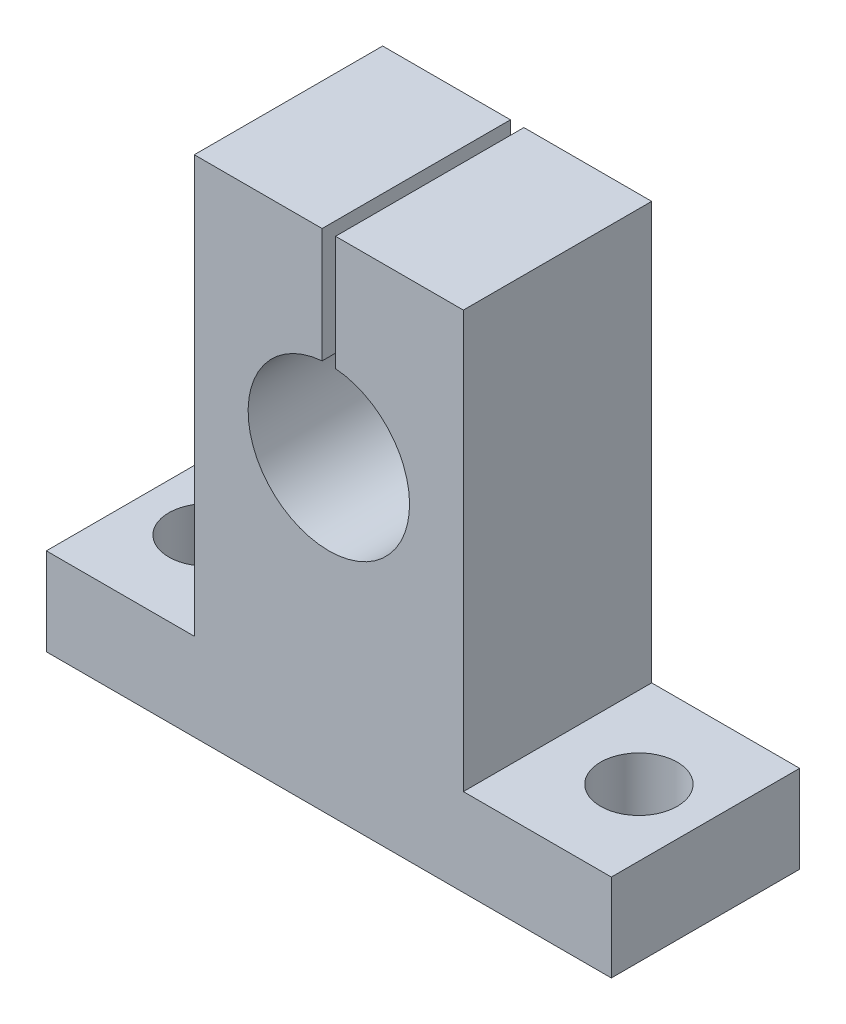
SolidWorks part; units mm, degrees
ref_plane "Ön Düzlem" through (0, 0, 0) normal (0, 0, 1) x (1, 0, 0)
ref_plane "Üst Düzlem" through (0, 0, 0) normal (0, 1, 0) x (1, 0, 0)
ref_plane "Sağ Düzlem" through (0, 0, 0) normal (1, 0, 0) x (0, 0, -1)
sketch "Çizim1" plane through (0, 0, 0) normal (0, 0, 1) x (1, 0, 0)
  line L0 (0, 66.7408) -> (0, -66.7408) construction
  line L1 (21, -23) -> (-21, -23)
  line L2 (-21, -23) -> (-21, -16.5)
  line L3 (-21, -16.5) -> (-10, -16.5)
  line L4 (-10, -16.5) -> (-10, 14.5)
  line L5 (-10, 14.5) -> (-0.5, 14.5)
  line L6 (-0.5, 14.5) -> (-0.5, 5.9791)
  line L7 (0.5, 14.5) -> (0.5, 5.9791)
  line L8 (10, 14.5) -> (0.5, 14.5)
  line L9 (10, -16.5) -> (10, 14.5)
  line L10 (21, -16.5) -> (10, -16.5)
  line L11 (21, -23) -> (21, -16.5)
  arc A0 (-0.5, 5.9791) -> (0.5, 5.9791) centre (0, 0) ccw
  point P18 (0, -23)
  dimension "D3" = 12
  dimension "D1" = 23
  dimension "D2" = 21
  dimension "D4" = 37.5
  dimension "D5" = 6.5
  dimension "D6" = 10
  dimension "D7" = 9.5
extrude "Yükseklik-Ekstrüzyon2" add sketch "Çizim1" along normal blind 14 contours L4 L5 L6 A0 L7 L8 L9 L10 L11 L1 L2 L3
sketch "Çizim2" plane through (0, -23, 0) normal (0, -1, 0) x (1, 0, 0)
  line L0 (0, 14) -> (0, 0) construction
  line L1 (21, 14) -> (-21, 14) construction
  line L2 (21, 0) -> (-21, 0) construction
  line L3 (-13.2, 7) -> (-13.2, 2.1812) construction
  line L4 (13.2, 7) -> (13.2, 2.7662) construction
  circle A0 centre (-16.05, 7) radius 2.85
  circle A1 centre (16.05, 7) radius 2.85
  point P10 (0, 7)
  dimension "D3" = 5.7
  dimension "D1" = 13.2
  dimension "D2" = 13.2
extrude "Kes-Ekstrüzyon1" cut sketch "Çizim2" against normal up to next and the other way through all
